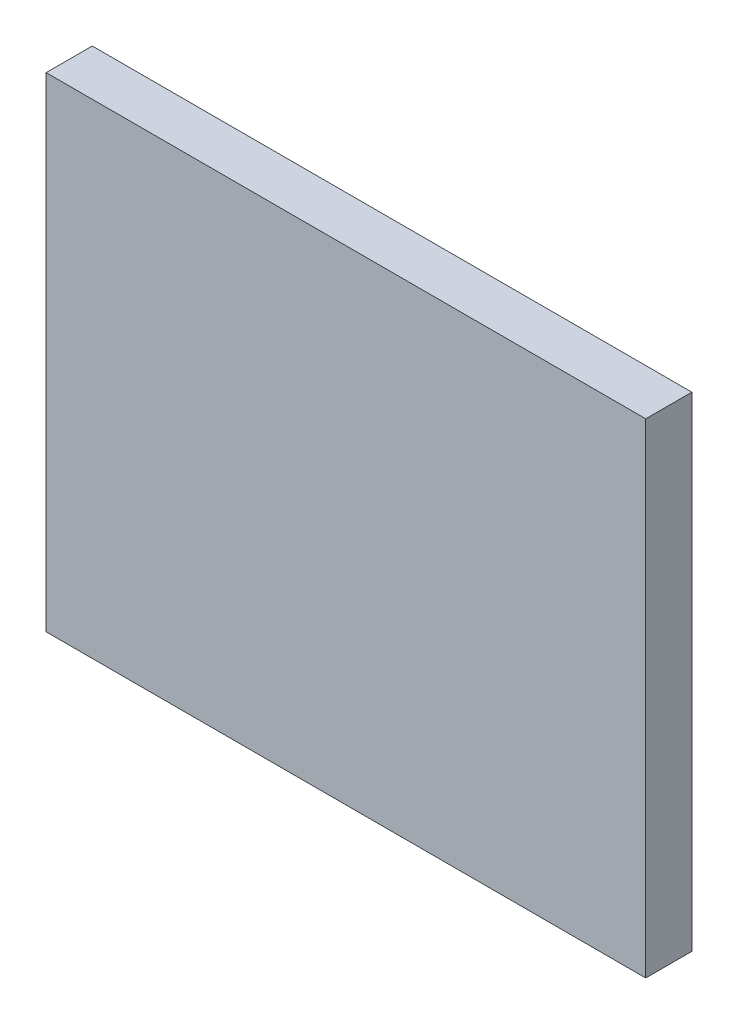
SolidWorks part; units mm, degrees
ref_plane "Plan de face" through (0, 0, 0) normal (0, 0, 1) x (1, 0, 0)
ref_plane "Plan de dessus" through (0, 0, 0) normal (0, 1, 0) x (1, 0, 0)
ref_plane "Plan de droite" through (0, 0, 0) normal (1, 0, 0) x (0, 0, -1)
sketch "Esquisse1" plane through (0, 0, 0) normal (0, 0, 1) x (1, 0, 0)
  line L1 (-75.1576, 30.9567) -> (54.8424, 30.9567)
  line L2 (-75.1576, 30.9567) -> (-75.1576, -74.0433)
  line L3 (-75.1576, -74.0433) -> (54.8424, -74.0433)
  line L4 (54.8424, 30.9567) -> (54.8424, -74.0433)
  dimension "D1" = 130
  dimension "D2" = 105
extrude "Boss.-Extru.1" add sketch "Esquisse1" along normal blind 10
